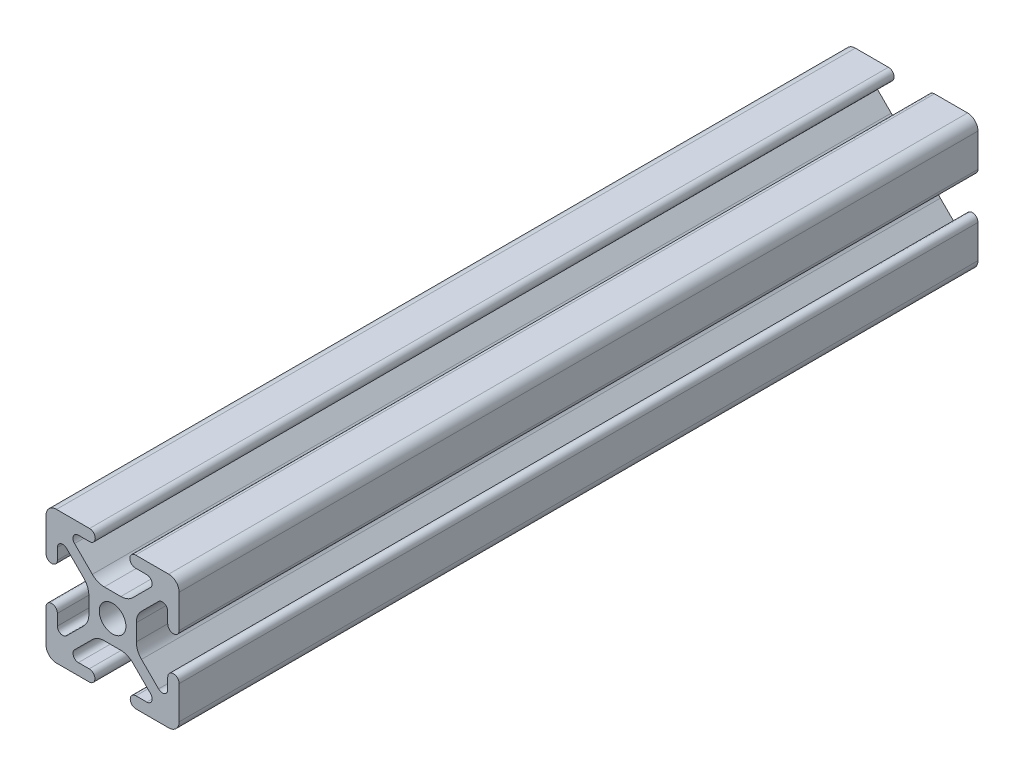
SolidWorks part; units mm, degrees
material "6005A-T61"
ref_plane "Front Plane" through (0, 0, 0) normal (0, 0, 1) x (1, 0, 0)
ref_plane "Top Plane" through (0, 0, 0) normal (0, 1, 0) x (1, 0, 0)
ref_plane "Right Plane" through (0, 0, 0) normal (1, 0, 0) x (0, 0, -1)
sketch "Sketch1" plane through (0, 0, 0) normal (0, 0, 1) x (1, 0, 0)
  line L0 (-8.6363, 7.1116) -> (-5.4322, 3.9121)
  line L1 (-4.455, 1.5554) -> (-4.455, -1.5554)
  line L2 (-5.4322, -3.9121) -> (-8.6363, -7.1116)
  line L3 (-10.36, -6.3969) -> (-10.36, -4.32)
  line L4 (-12.5, -4.32) -> (-12.5, -8.6518)
  line L5 (-12.5, -8.6518) -> (-12.5, -10.5371)
  line L6 (-10.5371, -12.5) -> (-8.4416, -12.5)
  line L7 (-8.4416, -12.5) -> (-4.3879, -12.5)
  line L8 (-4.3879, -10.36) -> (-6.42, -10.36)
  line L9 (-7.1337, -8.6353) -> (-3.7953, -5.3018)
  line L10 (-1.5554, -4.375) -> (1.5554, -4.375)
  line L11 (10.36, 4.32) -> (10.36, 6.3969)
  line L12 (12.5, 7.9913) -> (12.5, 4.32)
  line L13 (12.5, 10.5371) -> (12.5, 7.9913)
  line L14 (4.32, 12.5) -> (10.5371, 12.5)
  line L16 (6.42, 10.36) -> (4.32, 10.36)
  line L17 (3.7953, 5.3018) -> (7.1337, 8.6353)
  line L18 (7.1337, -8.6353) -> (3.7953, -5.3018)
  line L19 (4.3879, -10.36) -> (6.42, -10.36)
  line L20 (8.4416, -12.5) -> (4.3879, -12.5)
  line L21 (10.5371, -12.5) -> (8.4416, -12.5)
  line L22 (12.5, -8.6518) -> (12.5, -10.5371)
  line L23 (12.5, -4.32) -> (12.5, -8.6518)
  line L24 (10.36, -6.3969) -> (10.36, -4.32)
  line L25 (5.4322, -3.9121) -> (8.6363, -7.1116)
  line L26 (4.455, 1.5554) -> (4.455, -1.5554)
  line L27 (8.6363, 7.1116) -> (5.4322, 3.9121)
  line L28 (1.5554, 4.375) -> (-1.5554, 4.375)
  line L29 (-3.7953, 5.3018) -> (-7.1337, 8.6353)
  line L30 (-6.42, 10.36) -> (-4.32, 10.36)
  line L32 (-4.32, 12.5) -> (-10.5371, 12.5)
  line L33 (-12.5, 10.5371) -> (-12.5, 7.9913)
  line L34 (-12.5, 7.9913) -> (-12.5, 4.32)
  line L35 (-10.36, 4.32) -> (-10.36, 6.3969)
  line L36 (-15.7693, 0) -> (12.5, 0) construction
  line L37 (0, 13.9334) -> (0, -12.3541) construction
  circle A0 centre (0, 0) radius 2.5
  arc A1 (-8.6363, 7.1116) -> (-10.36, 6.3969) centre (-9.35, 6.3969) ccw
  arc A2 (-4.455, 1.5554) -> (-5.4322, 3.9121) centre (-7.7855, 1.5554) ccw
  arc A3 (-5.4322, -3.9121) -> (-4.455, -1.5554) centre (-7.7855, -1.5554) ccw
  arc A4 (-10.36, -6.3969) -> (-8.6363, -7.1116) centre (-9.35, -6.3969) ccw
  arc A5 (-10.36, -4.32) -> (-12.5, -4.32) centre (-11.43, -4.32) ccw
  arc A6 (-12.5, -10.5371) -> (-10.5371, -12.5) centre (-10.5371, -10.5371) ccw
  arc A7 (-4.3879, -12.5) -> (-4.3879, -10.36) centre (-4.3879, -11.43) ccw
  arc A8 (-7.1337, -8.6353) -> (-6.42, -10.36) centre (-6.42, -9.35) ccw
  arc A9 (-1.5554, -4.375) -> (-3.7953, -5.3018) centre (-1.5554, -7.545) ccw
  arc A10 (12.5, 4.32) -> (10.36, 4.32) centre (11.43, 4.32) cw
  arc A11 (10.5371, 12.5) -> (12.5, 10.5371) centre (10.5371, 10.5371) cw
  arc A12 (4.32, 10.36) -> (4.32, 12.5) centre (4.32, 11.43) cw
  arc A13 (6.42, 10.36) -> (7.1337, 8.6353) centre (6.42, 9.35) cw
  arc A14 (3.7953, 5.3018) -> (1.5554, 4.375) centre (1.5554, 7.545) cw
  arc A15 (1.5554, -4.375) -> (3.7953, -5.3018) centre (1.5554, -7.545) cw
  arc A16 (7.1337, -8.6353) -> (6.42, -10.36) centre (6.42, -9.35) cw
  arc A17 (4.3879, -12.5) -> (4.3879, -10.36) centre (4.3879, -11.43) cw
  arc A18 (12.5, -10.5371) -> (10.5371, -12.5) centre (10.5371, -10.5371) cw
  arc A19 (10.36, -4.32) -> (12.5, -4.32) centre (11.43, -4.32) cw
  arc A20 (10.36, -6.3969) -> (8.6363, -7.1116) centre (9.35, -6.3969) cw
  arc A21 (5.4322, -3.9121) -> (4.455, -1.5554) centre (7.7855, -1.5554) cw
  arc A22 (4.455, 1.5554) -> (5.4322, 3.9121) centre (7.7855, 1.5554) cw
  arc A23 (8.6363, 7.1116) -> (10.36, 6.3969) centre (9.35, 6.3969) cw
  arc A24 (-3.7953, 5.3018) -> (-1.5554, 4.375) centre (-1.5554, 7.545) ccw
  arc A25 (-6.42, 10.36) -> (-7.1337, 8.6353) centre (-6.42, 9.35) ccw
  arc A26 (-4.32, 10.36) -> (-4.32, 12.5) centre (-4.32, 11.43) ccw
  arc A27 (-10.5371, 12.5) -> (-12.5, 10.5371) centre (-10.5371, 10.5371) ccw
  arc A28 (-12.5, 4.32) -> (-10.36, 4.32) centre (-11.43, 4.32) ccw
  dimension "D4" = 14.86
  dimension "D5" = 2.14
  dimension "D6" = 6.5
  dimension "D7" = 8.75
  dimension "D8" = 1.01
  dimension "D9" = 3.17
  dimension "D14" = 5
  dimension "D1" = 25
  dimension "D2" = 8.91
  dimension "D3" = 12.5
  dimension "D12" = 2.14
extrude "Extrude1" add sketch "Sketch1" against normal blind 150
equation "\"WallThickness\"= 0.5cm"
equation "\"BottomPlateX\"= 3ft"
equation "\"BottomPlateZ\"= 2ft"
equation "\"BottomPlateHoleD\"=((\"ArmPlateX\")^2+(\"ArmPlateDepth\")^2)^.5+ 10mm"
equation "\"ActuatorPinD\"= 6.35mm"
equation "\"ActuatorPinL\"= 15cm"
equation "\"Box-X\"= 40cm"
equation "\"Box-Z\"= 20cm"
equation "\"Box-Y\"= 30cm"
equation "\"ArmPlateThickness\"= .125in"
equation "\"ArmPlateX\"= 18in"
equation "\"ArmPlateDepth\"= 7.1875in"
equation "\"DCMotor1D\"= 65mm"
equation "\"DCMotor1L\"= 215mm"
equation "\"DCMotor1ShaftL\"= 30mm"
equation "\"DCMotor2X\"= 68mm"
equation "\"DCMotor2D\"= 65mm"
equation "\"DCMotor2L\"= 208mm"
equation "\"DCMotor2ShaftL\"= 39mm"
equation "\"DCMotor2ShaftD\"= 15mm"
equation "\"BenchDepth\"= 5cm"
equation "\"BenchH\"= 10cm"
equation "\"BenchL\"= 15cm"
equation "\"PillowBlockW\"= 5cm"
equation "\"PillowBlockCenterH\"= \"DCMotor2X\"/2"
equation "\"EncoderRadius\"= 19mm"
equation "\"EncoderShaftL\"= 15mm"
equation "\"EncoderL\"= 33mm"
equation "\"EncoderHousingThickness\"= 7.5mm"
equation "\"TurntableID\"= 70mm"
equation "\"TurntableInner2*t\" = (\"TurntableOD\"-\"TurntableID\")*.25 - 1mm"
equation "\"TurntableInnerHoleRadius\"= \"TurntableID\"*.5 + \"TurntableInner2*t\"*.5"
equation "\"TurntableOD\"= 120mm"
equation "\"TurntableOuterHoleRadius\" = \"TurntableOD\"*.5 - ((\"TurntableOD\"-\"TurntableID\")*.25-.5mm)*.5"
equation "\"2525Height\" = 30cm"
equation "\"LENGTH@Extrude1\"=\"TurntableOD\"+3cm"
